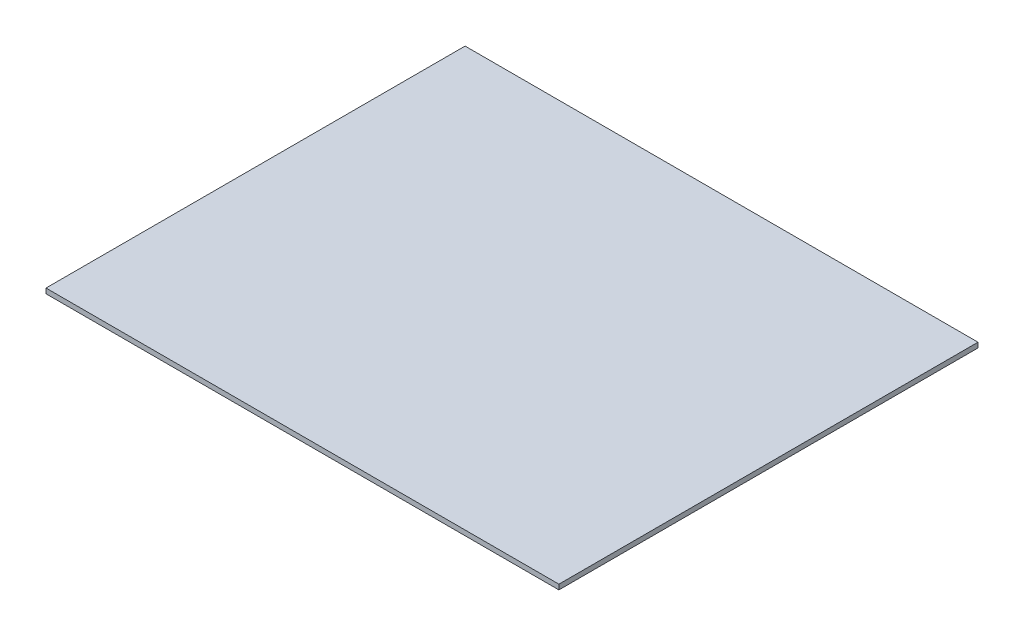
SolidWorks part; units mm, degrees
ref_plane "Front Plane" through (0, 0, 0) normal (0, 0, 1) x (1, 0, 0)
ref_plane "Top Plane" through (0, 0, 0) normal (0, 1, 0) x (1, 0, 0)
ref_plane "Right Plane" through (0, 0, 0) normal (1, 0, 0) x (0, 0, -1)
sketch "Sketch1" plane through (0, 0, 0) normal (0, 1, 0) x (1, 0, 0)
  line L1 (-205, 167.5) -> (205, 167.5)
  line L2 (-205, 167.5) -> (-205, -167.5)
  line L3 (-205, -167.5) -> (205, -167.5)
  line L4 (205, 167.5) -> (205, -167.5)
  line L5 (-205, 167.5) -> (205, -167.5) construction
  line L6 (-205, -167.5) -> (205, 167.5) construction
  point P0 (0, 0)
  dimension "D1" = 335
  dimension "D2" = 410
extrude "Boss-Extrude1" add sketch "Sketch1" along normal blind 4
